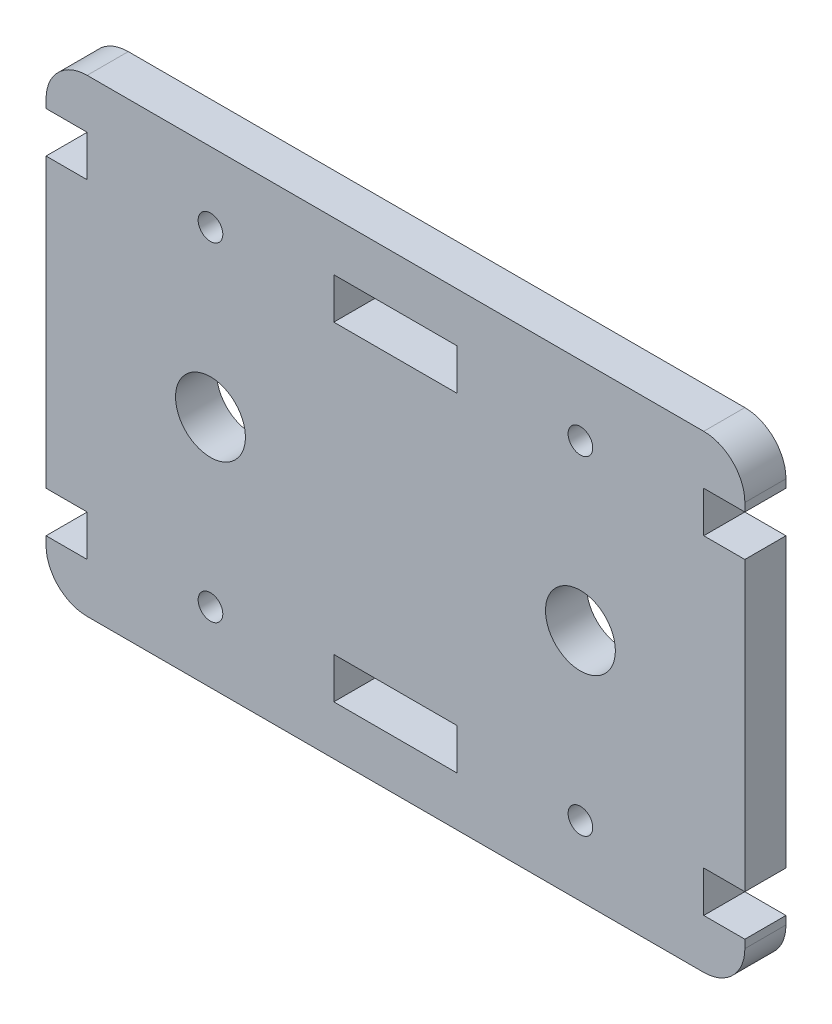
SolidWorks part; units mm, degrees
ref_plane "Plan de face" through (0, 0, 0) normal (0, 0, 1) x (1, 0, 0)
ref_plane "Plan de dessus" through (0, 0, 0) normal (0, 1, 0) x (1, 0, 0)
ref_plane "Plan de droite" through (0, 0, 0) normal (1, 0, 0) x (0, 0, -1)
sketch "Esquisse1" plane through (0, 0, 0) normal (0, 0, 1) x (1, 0, 0)
  line L0 (-20, 0) -> (20, 0)
  line L1 (20, 0) -> (20, 6)
  line L2 (20, 6) -> (15, 6)
  line L3 (15, 6) -> (15, 11)
  line L4 (15, 11) -> (20, 11)
  line L5 (20, 11) -> (20, 46)
  line L6 (20, 46) -> (15, 46)
  line L7 (15, 46) -> (15, 51)
  line L8 (15, 51) -> (20, 51)
  line L9 (20, 51) -> (20, 57)
  line L10 (20, 57) -> (-20, 57)
  line L11 (-20, 57) -> (-20, 51) construction
  line L12 (-20, 51) -> (-15, 51)
  line L13 (-15, 51) -> (-15, 46)
  line L14 (-15, 46) -> (-20, 46)
  line L15 (-20, 46) -> (-20, 11) construction
  line L16 (-20, 11) -> (-15, 11)
  line L17 (-15, 11) -> (-15, 6)
  line L18 (-15, 6) -> (-20, 6)
  line L19 (-20, 6) -> (-20, 0) construction
  line L20 (0, 0) -> (0, 57) construction
  line L21 (-15, 8.5) -> (15, 8.5) construction
  line L22 (15, 48.5) -> (-15, 48.5) construction
  line L23 (-20, 28.5) -> (20, 28.5) construction
  line L24 (-22.5, 57) -> (-22.5, 0) construction
  line L25 (-30, 46) -> (-25, 46)
  line L26 (-30, 51) -> (-30, 46)
  line L27 (-25, 51) -> (-30, 51)
  line L28 (-25, 57) -> (-25, 51) construction
  line L29 (-65, 57) -> (-25, 57)
  line L30 (-65, 51) -> (-65, 57)
  line L31 (-60, 51) -> (-65, 51)
  line L32 (-60, 46) -> (-60, 51)
  line L33 (-65, 46) -> (-60, 46)
  line L34 (-65, 11) -> (-65, 46)
  line L35 (-60, 11) -> (-65, 11)
  line L36 (-60, 6) -> (-60, 11)
  line L37 (-65, 6) -> (-60, 6)
  line L38 (-65, 0) -> (-65, 6)
  line L39 (-25, 0) -> (-65, 0)
  line L40 (-25, 6) -> (-25, 0) construction
  line L41 (-30, 6) -> (-25, 6)
  line L42 (-30, 11) -> (-30, 6)
  line L43 (-25, 11) -> (-30, 11)
  line L44 (-25, 51) -> (-20, 51)
  line L45 (-20, 46) -> (-25, 46)
  line L46 (-25, 11) -> (-20, 11)
  line L47 (-20, 6) -> (-25, 6)
  line L48 (-25, 57) -> (-20, 57)
  line L49 (-20, 0) -> (-25, 0)
  circle A0 centre (0, 48.5) radius 1.5
  circle A1 centre (0, 8.5) radius 1.5
  circle A2 centre (0, 28.5) radius 4.25
  circle A3 centre (-20, 28.5) radius 1.6 construction
  circle A4 centre (20, 28.5) radius 1.6 construction
  circle A5 centre (-45, 8.5) radius 1.5
  circle A6 centre (-45, 28.5) radius 4.25
  circle A7 centre (-45, 48.5) radius 1.5
  dimension "D6" = 3
  dimension "D7" = 3
  dimension "D8" = 8.5
  dimension "D10" = 3.2
  dimension "D12" = 5
  dimension "D1" = 5
  dimension "D2" = 30
  dimension "D3" = 40
  dimension "D4" = 6
  dimension "D5" = 40
  dimension "D9" = 40
  dimension "D11" = 20
extrude "Boss.-Extru.1" add sketch "Esquisse1" along normal blind 5
fillet "Congé1" radius 5 4 edges at (20, 57, 2.5) (20, 0, 2.5) (-65, 0, 2.5) (-65, 57, 2.5)
